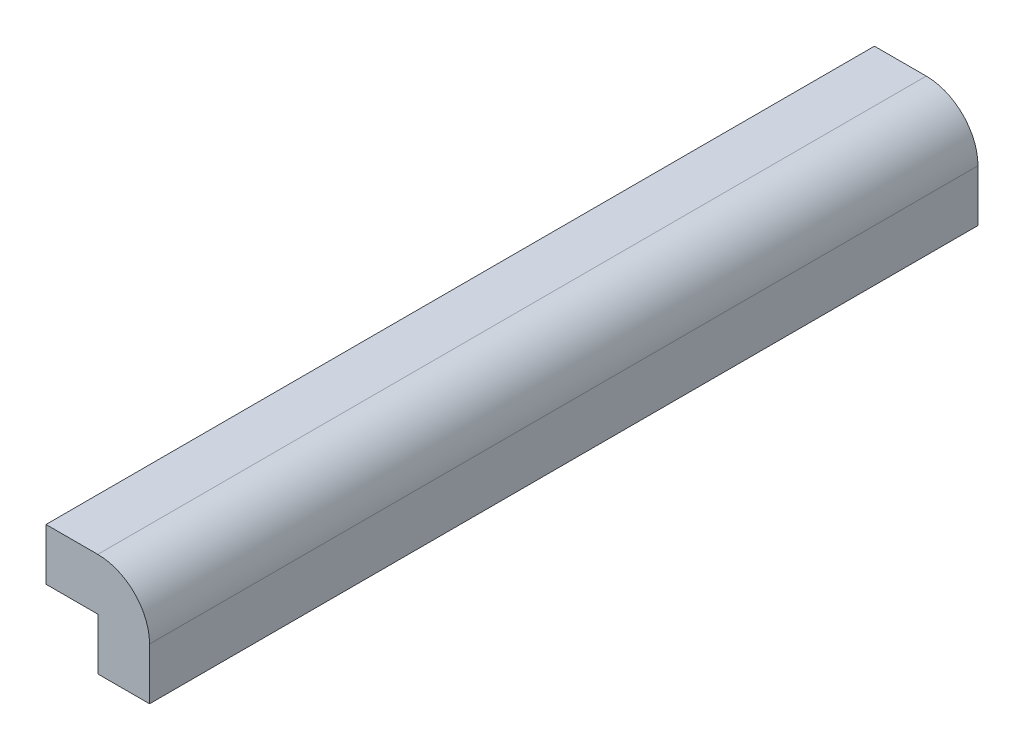
SolidWorks part; units mm, degrees
ref_plane "Front Plane" through (0, 0, 0) normal (0, 0, 1) x (1, 0, 0)
ref_plane "Top Plane" through (0, 0, 0) normal (0, 1, 0) x (1, 0, 0)
ref_plane "Right Plane" through (0, 0, 0) normal (1, 0, 0) x (0, 0, -1)
sketch "Sketch1" plane through (0, 0, 0) normal (0, 0, 1) x (1, 0, 0)
  line L1 (0, 0) -> (-8, 0)
  line L3 (0, 8) -> (-8, 8)
  line L4 (-8, 0) -> (-8, 8)
  line L6 (0, 0) -> (0, -8)
  line L7 (0, -8) -> (8, -8)
  line L8 (8, 0) -> (8, -8)
  arc A0 (0, 8) -> (8, 0) centre (0, 0) cw
  dimension "D5" = 8
  dimension "D1" = 8
  dimension "D2" = 8
  dimension "D3" = 8
  dimension "D4" = 8
extrude "Boss-Extrude1" add sketch "Sketch1" along normal blind 128
